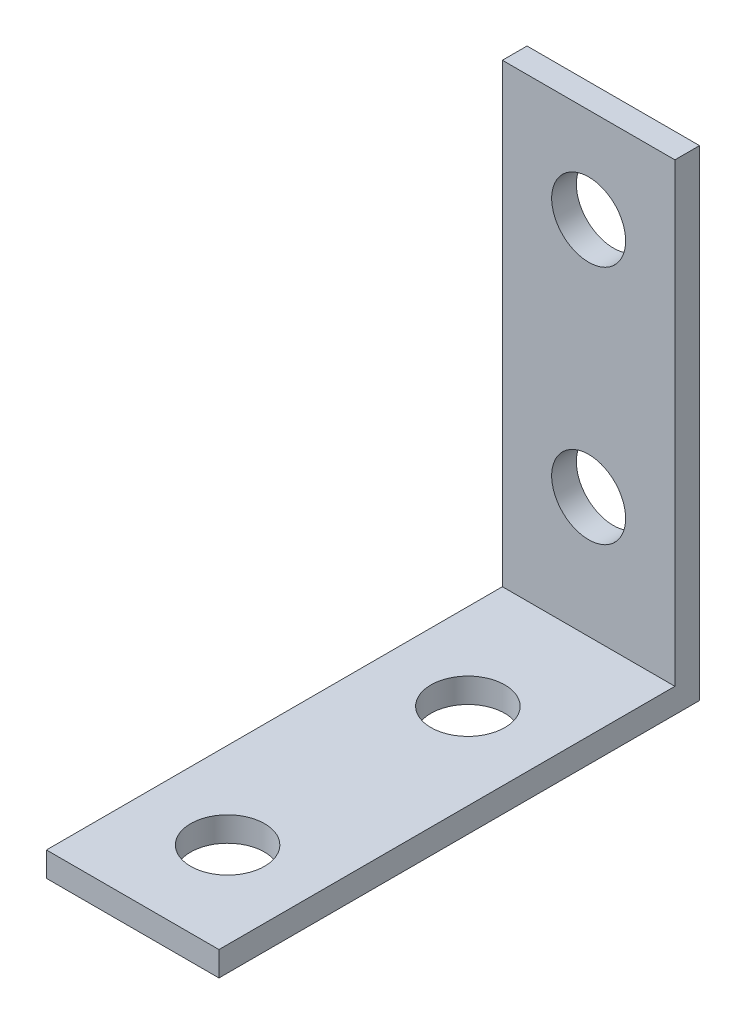
SolidWorks part; units mm, degrees
ref_plane "Front Plane" through (0, 0, 0) normal (0, 0, 1) x (1, 0, 0)
ref_plane "Top Plane" through (0, 0, 0) normal (0, 1, 0) x (1, 0, 0)
ref_plane "Right Plane" through (0, 0, 0) normal (1, 0, 0) x (0, 0, -1)
sketch "Sketch1" plane through (0, 0, 0) normal (1, 0, 0) x (0, 0, -1)
  line L0 (-21.4943, 2) -> (15.5057, 2)
  line L1 (15.5057, 2) -> (15.5057, 39)
  line L2 (15.5057, 39) -> (17.5057, 39)
  line L3 (17.5057, 39) -> (17.5057, 0)
  line L4 (17.5057, 0) -> (-21.4943, 0)
  line L5 (-21.4943, 0) -> (-21.4943, 2)
  dimension "D1" = 2
  dimension "D2" = 2
  dimension "D3" = 39
  dimension "D4" = 39
extrude "Boss-Extrude1" add sketch "Sketch1" along normal blind 14
sketch "Sketch2" plane through (0, 2, 0) normal (0, 1, 0) x (1, 0, 0)
  line L0 (7, -21.4943) -> (7, 15.5057) construction
  line L1 (14, -21.4943) -> (0, -21.4943) construction
  line L2 (14, 15.5057) -> (0, 15.5057) construction
  circle A0 centre (7, -13.7943) radius 3
  circle A1 centre (7, 5.7057) radius 3
  dimension "D1" = 6
  dimension "D2" = 19.5
  dimension "D3" = 31.3
extrude "Cut-Extrude1" cut sketch "Sketch2" against normal through all
sketch "Sketch3" plane through (0, 0, -15.5057) normal (0, 0, 1) x (1, 0, 0)
  line L0 (7, 2) -> (7, 39) construction
  line L1 (14, 2) -> (0, 2) construction
  line L2 (14, 39) -> (0, 39) construction
  circle A0 centre (7, 11.8) radius 3
  circle A1 centre (7, 31.3) radius 3
  dimension "D1" = 6
  dimension "D2" = 19.5
  dimension "D3" = 31.3
extrude "Cut-Extrude2" cut sketch "Sketch3" against normal through all
